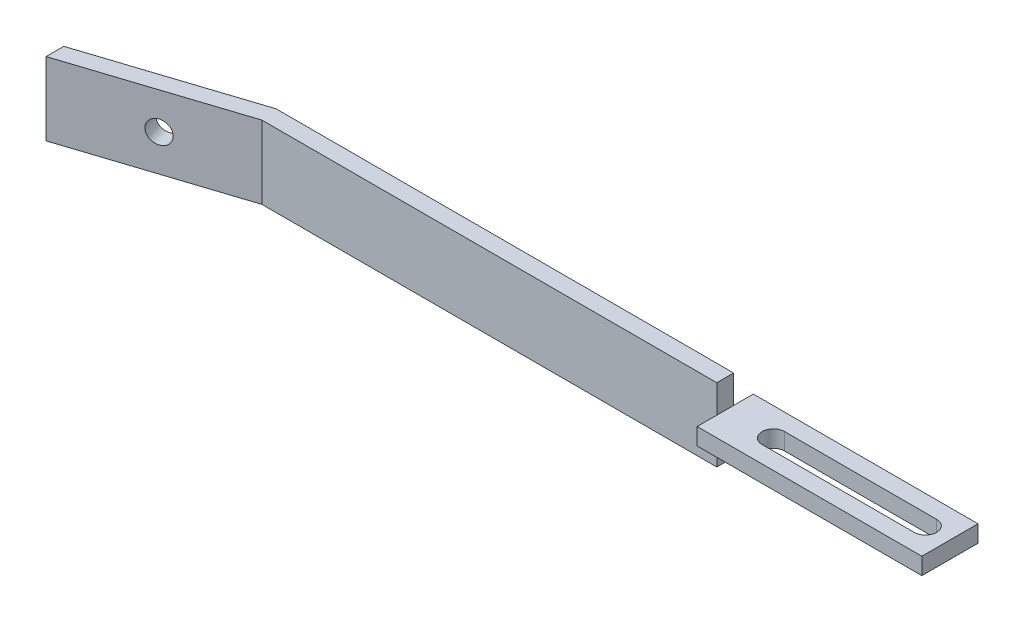
SolidWorks part; units mm, degrees
ref_plane "Front Plane" through (0, 0, 0) normal (0, 0, 1) x (1, 0, 0)
ref_plane "Top Plane" through (0, 0, 0) normal (0, 1, 0) x (1, 0, 0)
ref_plane "Right Plane" through (0, 0, 0) normal (1, 0, 0) x (0, 0, -1)
sketch "Sketch1" plane through (0, 0, 0) normal (0, 0, 1) x (1, 0, 0)
  line L1 (-75, 6.5) -> (75, 6.5)
  line L2 (-75, 6.5) -> (-75, -6.5)
  line L3 (-75, -6.5) -> (75, -6.5)
  line L4 (75, 6.5) -> (75, -6.5)
  line L5 (-75, 6.5) -> (75, -6.5) construction
  line L6 (-75, -6.5) -> (75, 6.5) construction
  point P0 (0, 0)
  dimension "D1" = 13
  dimension "D2" = 150
extrude "Boss-Extrude1" add sketch "Sketch1" along normal blind 40
sketch "Sketch2" plane through (0, -6.5, 0) normal (0, -1, 0) x (1, 0, 0)
  line L0 (-75, 9.2705) -> (-46.4683, 0)
  line L1 (-75, 40) -> (-75, 0) construction
  line L2 (-75, 0) -> (75, 0) construction
  line L3 (-75, 9.2705) -> (-75, 0)
  line L4 (-75, 0) -> (-46.4683, 0)
  dimension "D1" = 30
  dimension "D2" = 162
extrude "Cut-Extrude1" cut sketch "Sketch2" against normal blind 40
sketch "Sketch3" plane through (0, -6.5, 0) normal (0, -1, 0) x (1, 0, 0)
  line L0 (-75, 12.4249) -> (-45.9932, 3)
  line L1 (-75, 40) -> (-75, 9.2705) construction
  line L2 (75, 40) -> (75, 0) construction
  line L3 (75, 3) -> (-45.9932, 3)
  line L4 (-46.4683, 0) -> (-75, 9.2705) construction
  line L5 (-46.4683, 0) -> (75, 0) construction
  line L6 (-75, 12.4249) -> (-75, 40)
  line L7 (-75, 40) -> (75, 40)
  line L8 (75, 40) -> (75, 3)
  dimension "D1" = 3
  dimension "D2" = 3
extrude "Cut-Extrude3" cut sketch "Sketch3" against normal through all
sketch "Sketch4" plane through (0, 0, 0) normal (0, 0, 1) x (1, 0, 0)
  line L0 (75, 6.5) -> (75, -6.5) construction
  line L1 (75, 1.5) -> (35, 1.5)
  line L2 (75, 1.5) -> (75, -1.5)
  line L3 (75, -1.5) -> (35, -1.5)
  line L4 (35, 1.5) -> (35, -1.5)
  line L5 (-46.4683, -6.5) -> (75, -6.5) construction
  line L6 (75, 6.5) -> (-46.4683, 6.5) construction
  dimension "D1" = 5
  dimension "D2" = 5
  dimension "D3" = 40
extrude "Boss-Extrude2" add sketch "Sketch4" along normal blind 6.5
sketch "Sketch5" plane through (0, 0, 3) normal (0, 0, 1) x (1, 0, 0)
  line L0 (35, -1.5) -> (35, -6.5)
  line L1 (-45.9932, -6.5) -> (75, -6.5) construction
  line L2 (35, -6.5) -> (75, -6.5)
  line L3 (75, -6.5) -> (75, -1.5)
  line L4 (75, -1.5) -> (35, -1.5)
  line L5 (35, 1.5) -> (35, 6.5)
  line L6 (-45.9932, 6.5) -> (75, 6.5) construction
  line L7 (35, 6.5) -> (75, 6.5)
  line L8 (75, 6.5) -> (75, 1.5)
  line L9 (75, 1.5) -> (35, 1.5)
extrude "Cut-Extrude4" cut sketch "Sketch5" against normal through all and the other way through all
sketch "Sketch6" plane through (0, 0, 0) normal (0, 0, -1) x (-1, 0, 0)
  line L1 (-75, -1.5) -> (-35, -1.5)
  line L2 (-75, -1.5) -> (-75, 1.5)
  line L3 (-75, 1.5) -> (-35, 1.5)
  line L4 (-35, -1.5) -> (-35, 1.5)
extrude "Boss-Extrude3" add sketch "Sketch6" along normal blind 3.5
sketch "Sketch7" plane through (0, 1.5, 0) normal (0, 1, 0) x (1, 0, 0)
  line L0 (70.6387, -1.5) -> (43.5615, -1.5) construction
  line L1 (70.6387, -3.5) -> (43.5615, -3.5)
  line L2 (70.6387, 0.5) -> (43.5615, 0.5)
  line L3 (35, 3.5) -> (75, 3.5) construction
  arc A0 (70.6387, -3.5) -> (70.6387, 0.5) centre (70.6387, -1.5) ccw
  arc A1 (43.5615, 0.5) -> (43.5615, -3.5) centre (43.5615, -1.5) ccw
  point P2 (57.1001, -1.5)
  dimension "D1" = 2
  dimension "D2" = 5
extrude "Cut-Extrude6" cut sketch "Sketch7" against normal blind 6.5
sketch "Sketch8" plane through (-4.4373, 0, -13.6567) normal (-0.309, 0, -0.9511) x (-0.9511, 0, 0.309)
  line L1 (44.194, 6.5) -> (74.194, 6.5) construction
  line L2 (44.194, -6.5) -> (44.194, 6.5) construction
  circle A0 centre (59.194, 0) radius 2
  dimension "D1" = 4
  dimension "D2" = 6.5
  dimension "D3" = 15
extrude "Cut-Extrude7" cut sketch "Sketch8" against normal blind 6.5
